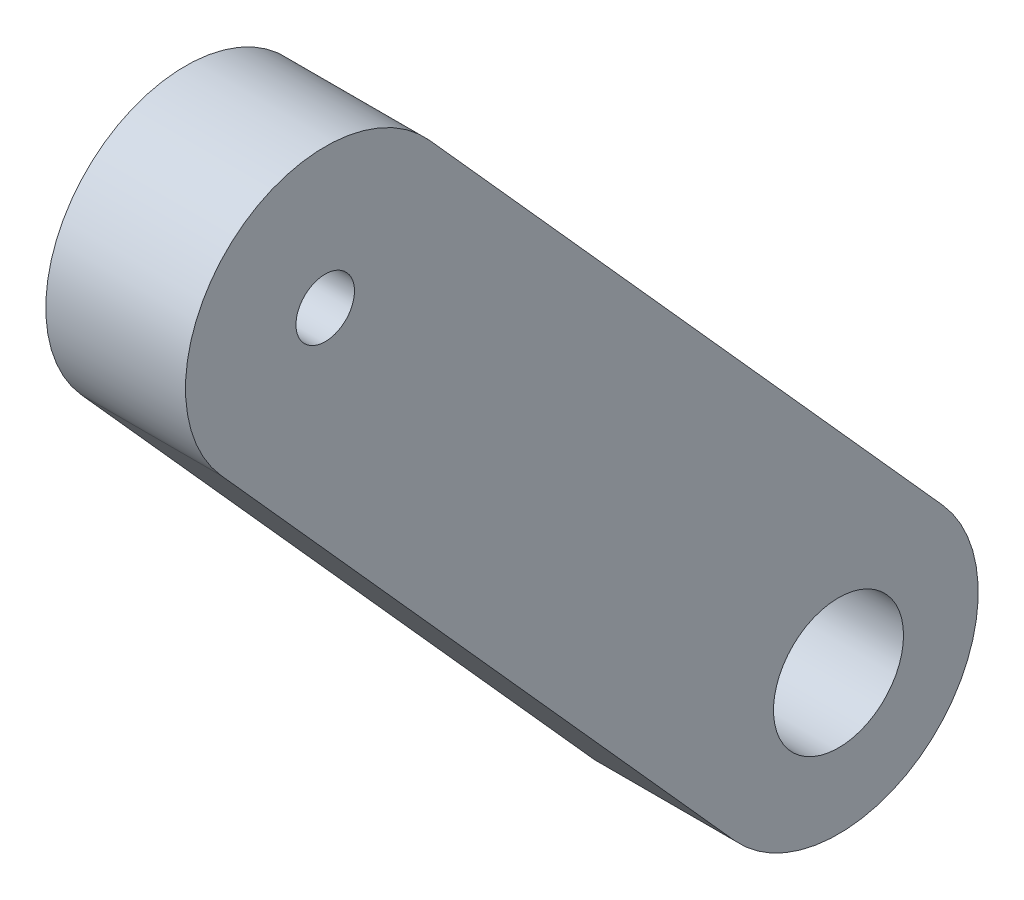
SolidWorks part; units mm, degrees
material "ABS"
ref_plane "Front Plane" through (0, 0, 0) normal (0, 0, 1) x (1, 0, 0)
ref_plane "Top Plane" through (0, 0, 0) normal (0, 1, 0) x (1, 0, 0)
ref_plane "Right Plane" through (0, 0, 0) normal (1, 0, 0) x (0, 0, -1)
sketch "Sketch1" plane through (-23.0628, 0, 0) normal (1, 0, 0) x (0, 0, -1)
  line L0 (-21.1768, 13.2245) -> (-3.6332, -6.35) construction
  line L1 (-17.6208, 16.4115) -> (-0.0772, -3.1629)
  line L2 (-24.7328, 10.0374) -> (-7.1892, -9.5371)
  circle A0 centre (-3.6332, -6.35) radius 2.2225 construction
  circle A1 centre (-3.6332, -6.35) radius 2.2225
  circle A2 centre (-21.1768, 13.2245) radius 1 construction
  circle A3 centre (-21.1768, 13.2245) radius 1
  arc A4 (-17.6208, 16.4115) -> (-24.7328, 10.0374) centre (-21.1768, 13.2245) ccw
  arc A5 (-7.1892, -9.5371) -> (-0.0772, -3.1629) centre (-3.6332, -6.35) ccw
  point P6 (-12.405, 3.4372)
  dimension "D1" = 4.7752
extrude "Boss-Extrude1" add sketch "Sketch1" along normal blind 4.7752
